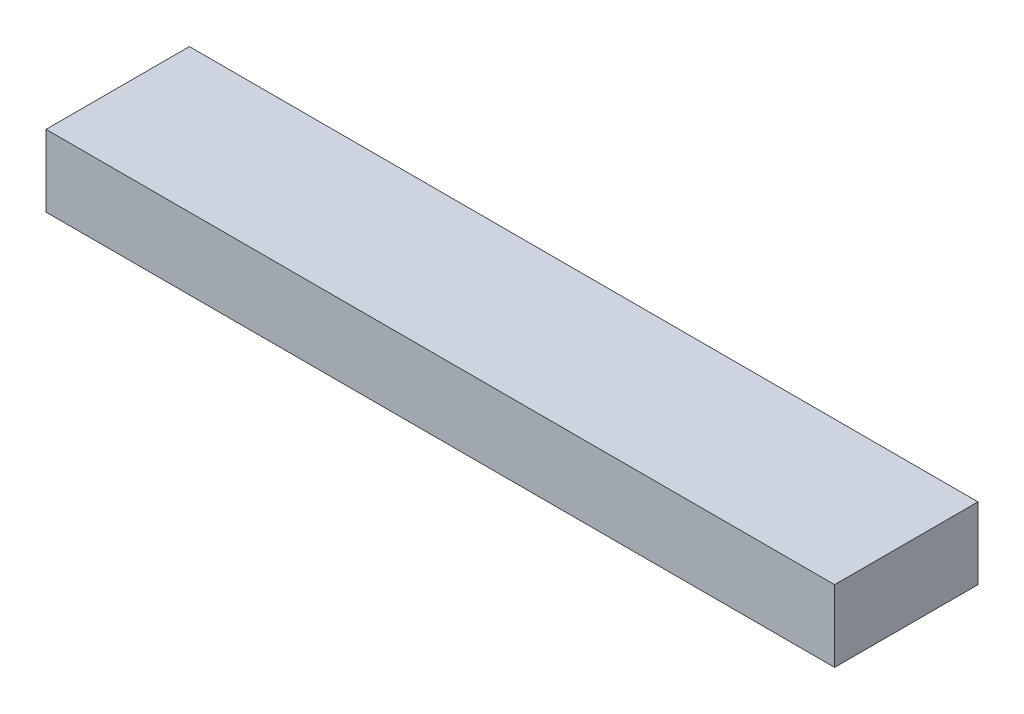
SolidWorks part; units mm, degrees
material "Pure Gold"
ref_plane "Front Plane" through (0, 0, 0) normal (0, 0, 1) x (1, 0, 0)
ref_plane "Top Plane" through (0, 0, 0) normal (0, 1, 0) x (1, 0, 0)
ref_plane "Right Plane" through (0, 0, 0) normal (1, 0, 0) x (0, 0, -1)
sketch "Sketch1" plane through (0, 0, 0) normal (0, 1, 0) x (1, 0, 0)
  line L1 (0, 0) -> (-55, 0)
  line L2 (0, 0) -> (0, 10)
  line L3 (0, 10) -> (-55, 10)
  line L4 (-55, 0) -> (-55, 10)
  dimension "D1" = 10
  dimension "D2" = 55
extrude "Boss-Extrude1" add sketch "Sketch1" along normal blind 5
